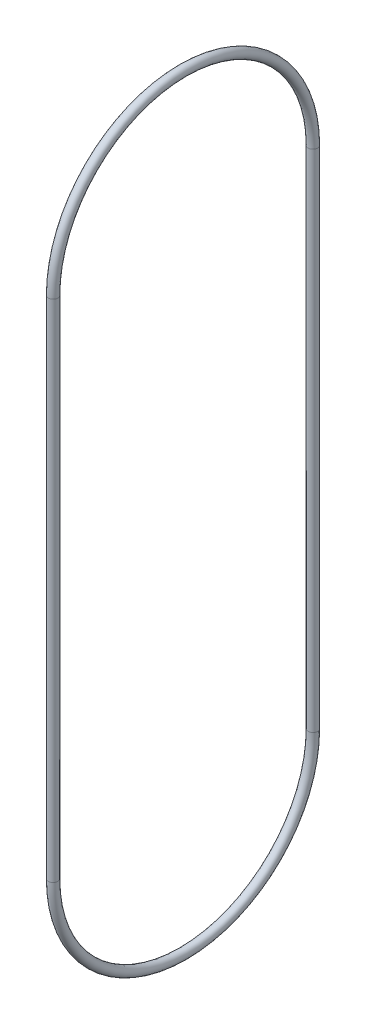
SolidWorks part; units mm, degrees
material "Alloy Steel"
ref_plane "Front Plane" through (0, 0, 0) normal (0, 0, 1) x (1, 0, 0)
ref_plane "Top Plane" through (0, 0, 0) normal (0, 1, 0) x (1, 0, 0)
ref_plane "Right Plane" through (0, 0, 0) normal (1, 0, 0) x (0, 0, -1)
sketch "Sketch2" plane through (0, 0, 0) normal (1, 0, 0) x (0, 0, -1)
  line L0 (0, 126.5482) -> (0, 0) construction
  line L1 (32.5437, 126.5482) -> (32.5437, 0)
  line L2 (-32.5437, 126.5482) -> (-32.5437, 0)
  arc A0 (-32.5437, 0) -> (32.5437, 0) centre (0, 0) ccw
  arc A1 (32.5437, 126.5482) -> (-32.5437, 126.5482) centre (0, 126.5482) ccw
  point P1 (0, 0)
  dimension "D1" = 65.0875
  dimension "D2" = 126.5482
sketch "Sketch3" plane through (0, 0, 0) normal (0, 1, 0) x (1, 0, 0)
  circle A0 centre (0, -32.5437) radius 1.1906
  dimension "D1" = 2.3813
sweep "Sweep1" add profiles "Sketch3" path "Sketch2"
